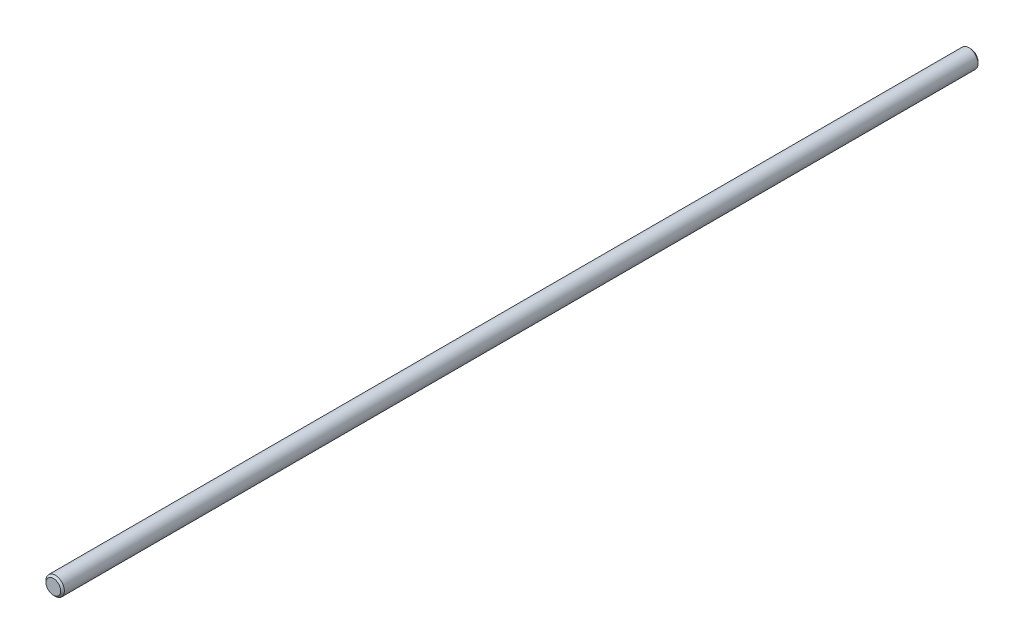
SolidWorks part; units mm, degrees
ref_plane "Front" through (0, 0, 0) normal (0, 0, 1) x (1, 0, 0)
ref_plane "Top" through (0, 0, 0) normal (0, 1, 0) x (1, 0, 0)
ref_plane "Right" through (0, 0, 0) normal (1, 0, 0) x (0, 0, -1)
sketch "Sketch1" plane through (0, 0, 0) normal (0, 0, 1) x (1, 0, 0)
  circle A0 centre (0, 0) radius 10
  dimension "D1" = 20
extrude "Extrude1" add sketch "Sketch1" along normal mid plane 1000
chamfer "Chamfer1" distance 2 angle 45 2 edges at (10, 0, -500) (10, 0, 500)
equation "\"D1@Chamfer1\" = \"D1@Sketch1\" * .1"
